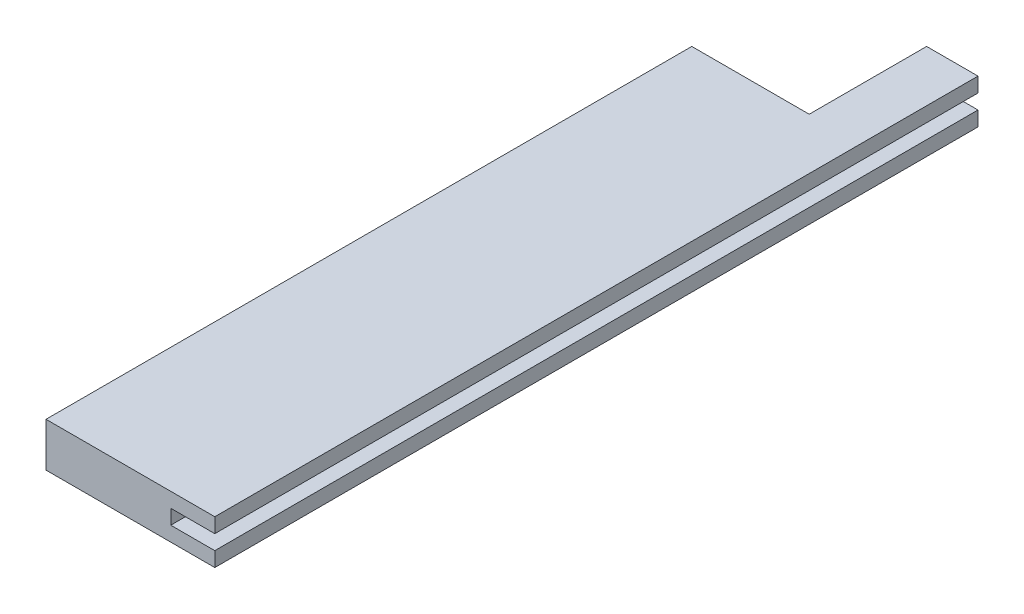
SolidWorks part; units mm, degrees
ref_plane "Front" through (0, 0, 0) normal (0, 0, 1) x (1, 0, 0)
ref_plane "Top" through (0, 0, 0) normal (0, 1, 0) x (1, 0, 0)
ref_plane "Right" through (0, 0, 0) normal (1, 0, 0) x (0, 0, -1)
sketch "Sketch1" plane through (0, 0, 0) normal (0, 1, 0) x (1, 0, 0)
  line L0 (-56.7627, -101.3183) -> (16.2623, -101.3183)
  line L1 (16.2623, -101.3183) -> (16.2623, 228.8817)
  line L2 (16.2623, 228.8817) -> (-5.9627, 228.8817)
  line L3 (-5.9627, 228.8817) -> (-5.9627, 178.0817)
  line L4 (-5.9627, 178.0817) -> (-56.7627, 178.0817)
  line L5 (-56.7627, 178.0817) -> (-56.7627, -101.3183)
  dimension "D1" = 330.2
  dimension "D2" = 279.4
  dimension "D3" = 50.8
  dimension "D4" = 73.025
extrude "Boss-Extrude1" add sketch "Sketch1" along normal mid plane 19.05 contours L4 L5 L0 L1 L2 L3
sketch "Sketch2" plane through (0, 0, 101.3183) normal (0, 0, 1) x (1, 0, 0)
  line L0 (50, 0) -> (-50, 0) construction
  line L1 (-2.7877, -3.175) -> (16.2623, -3.175)
  line L2 (-2.7877, -3.175) -> (-2.7877, 3.175)
  line L3 (-2.7877, 3.175) -> (16.2623, 3.175)
  line L4 (16.2623, -3.175) -> (16.2623, 3.175)
  line L5 (-2.7877, -3.175) -> (16.2623, 3.175) construction
  line L6 (-2.7877, 3.175) -> (16.2623, -3.175) construction
  line L7 (16.2623, 9.525) -> (16.2623, -9.525) construction
  point P0 (6.7373, 0)
  dimension "D1" = 6.35
  dimension "D2" = 19.05
extrude "Cut-Extrude1" cut sketch "Sketch2" against normal up to next
